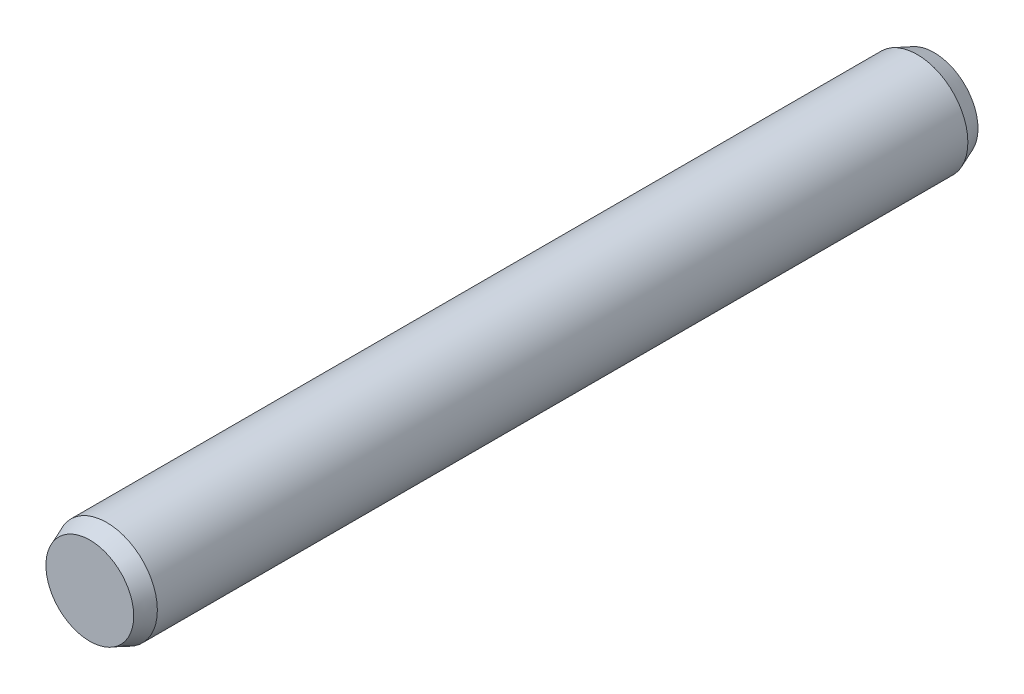
SolidWorks part; units mm, degrees
ref_plane "Front Plane" through (0, 0, 0) normal (0, 0, 1) x (1, 0, 0)
ref_plane "Top Plane" through (0, 0, 0) normal (0, 1, 0) x (1, 0, 0)
ref_plane "Right Plane" through (0, 0, 0) normal (1, 0, 0) x (0, 0, -1)
sketch "Sketch1" plane through (0, 0, 0) normal (0, 0, 1) x (1, 0, 0)
  circle A0 centre (0, 0) radius 1.5
  dimension "D1" = 3
extrude "Boss-Extrude1" add sketch "Sketch1" along normal mid plane 25
chamfer "Chamfer1" distance 0.5 distance2 0.2 1 edges at (1.5, 0, 12.5)
chamfer "Chamfer2" distance 0.2 distance2 0.5 1 edges at (1.5, 0, -12.5)
